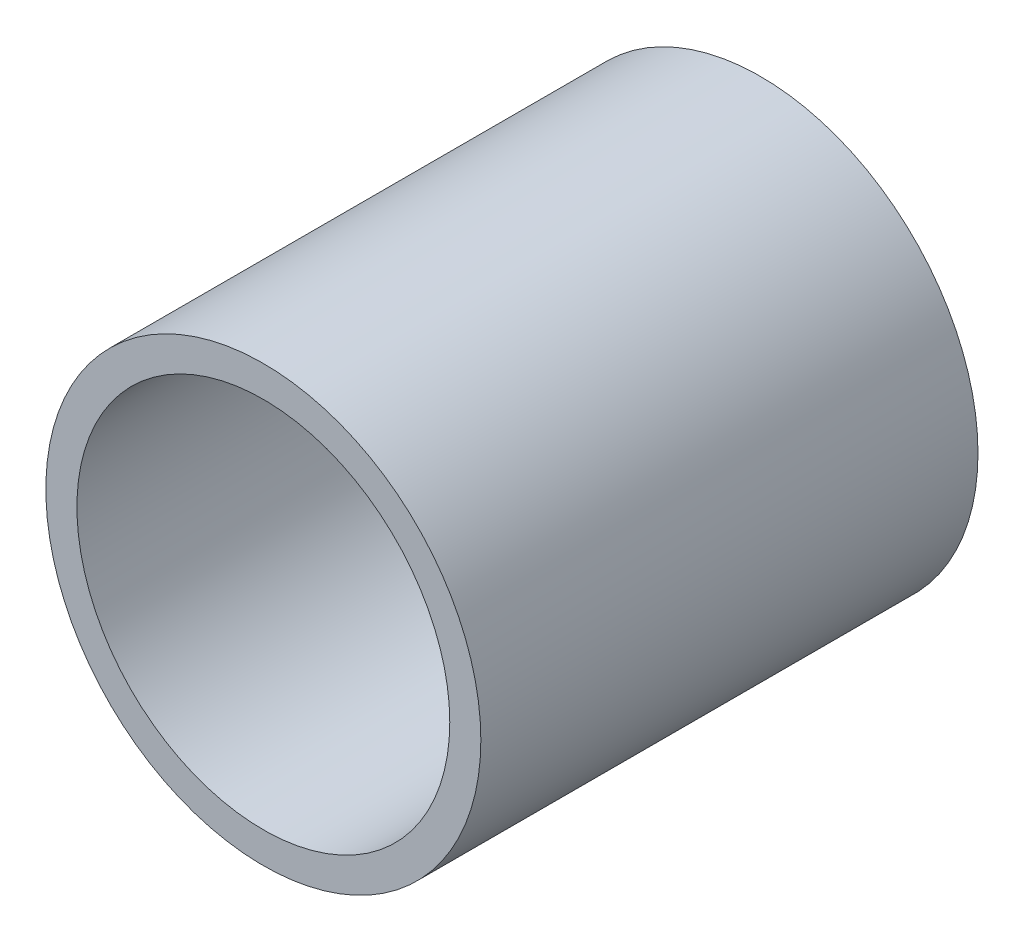
SolidWorks part; units mm, degrees
ref_plane "Front Plane" through (0, 0, 0) normal (0, 0, 1) x (1, 0, 0)
ref_plane "Top Plane" through (0, 0, 0) normal (0, 1, 0) x (1, 0, 0)
ref_plane "Right Plane" through (0, 0, 0) normal (1, 0, 0) x (0, 0, -1)
sketch "Sketch1" plane through (0, 0, 0) normal (0, 0, 1) x (1, 0, 0)
  circle A0 centre (0, 0) radius 6
  circle A1 centre (0, 0) radius 7
  dimension "D1" = 12
  dimension "D2" = 14
extrude "Boss-Extrude1" add sketch "Sketch1" along normal blind 16
